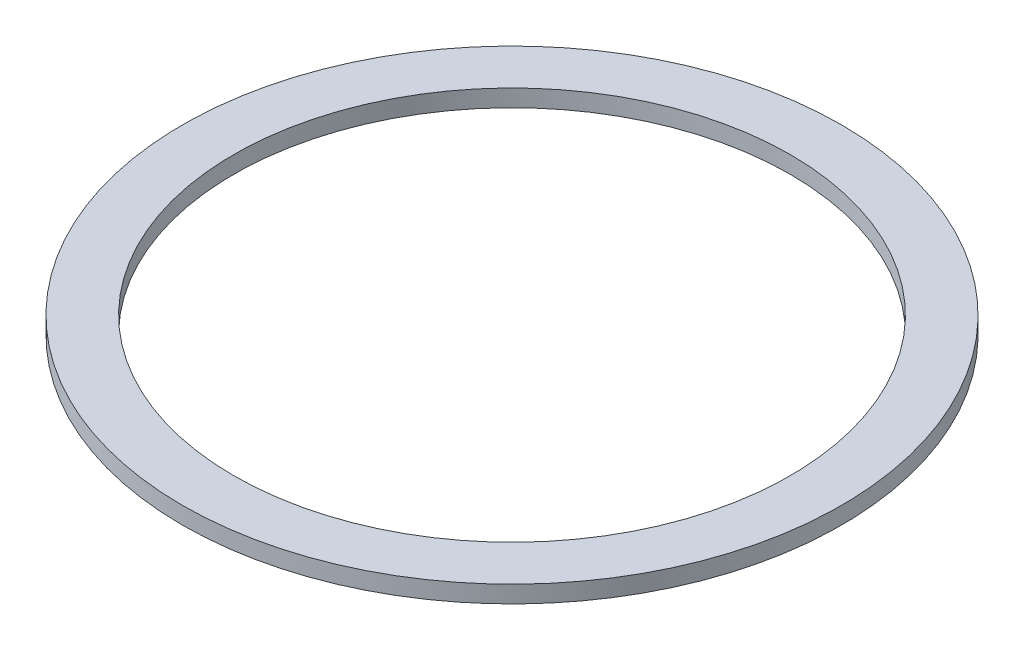
SolidWorks part; units mm, degrees
material "Pine"
ref_plane "Front Plane" through (0, 0, 0) normal (0, 0, 1) x (1, 0, 0)
ref_plane "Top Plane" through (0, 0, 0) normal (0, 1, 0) x (1, 0, 0)
ref_plane "Right Plane" through (0, 0, 0) normal (1, 0, 0) x (0, 0, -1)
sketch "Sketch1" plane through (0, 0, 0) normal (0, 1, 0) x (1, 0, 0)
  circle A0 centre (0, 0) radius 192.5
  circle A1 centre (0, 0) radius 162.5
  dimension "D1" = 385
  dimension "D2" = 325
extrude "Boss-Extrude1" add sketch "Sketch1" along normal mid plane 10
